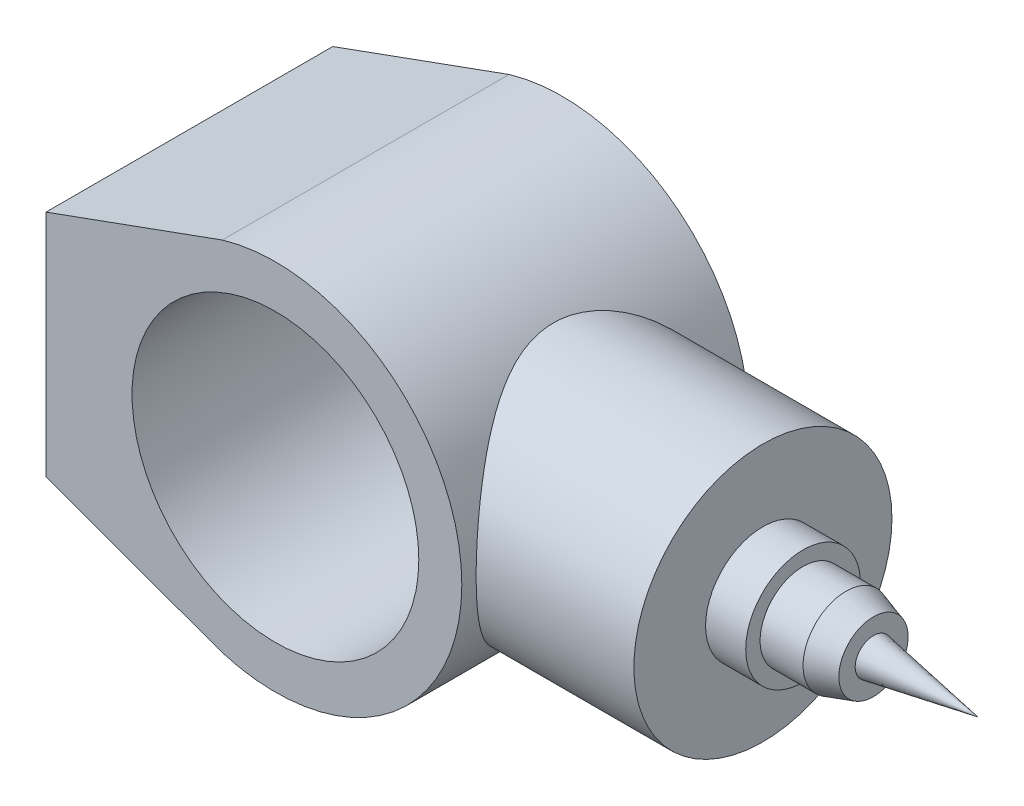
SolidWorks part; units mm, degrees
ref_plane "Front Plane" through (0, 0, 0) normal (0, 0, 1) x (1, 0, 0)
ref_plane "Top Plane" through (0, 0, 0) normal (0, 1, 0) x (1, 0, 0)
ref_plane "Right Plane" through (0, 0, 0) normal (1, 0, 0) x (0, 0, -1)
sketch "Sketch1" plane through (0, 0, 0) normal (0, 0, 1) x (1, 0, 0)
  line L0 (-80, -40) -> (-80, 40)
  line L1 (-80, 40) -> (-18.5119, 62.3082)
  line L2 (-80, -40) -> (-18.5119, -62.3082)
  arc A0 (-18.5119, -62.3082) -> (-18.5119, 62.3082) centre (0, 0) ccw
  circle A1 centre (0, 0) radius 50
  point P7 (-80, 0)
  dimension "D1" = 130
  dimension "D2" = 100
  dimension "D3" = 80
  dimension "D4" = 80
extrude "Boss-Extrude1" add sketch "Sketch1" along normal mid plane 100
ref_plane "Plane1" through (120, 0, 0) normal (1, 0, 0) x (0, 0, -1)
sketch "Sketch2" plane through (120, 0, 0) normal (1, 0, 0) x (0, 0, -1)
  circle A0 centre (0, 0) radius 45
  dimension "D1" = 90
extrude "Boss-Extrude2" add sketch "Sketch2" against normal up to next
sketch "Sketch3" plane through (0, 0, 0) normal (0, 0, 1) x (1, 0, 0)
  line L0 (0, 0) -> (320.8767, 0) construction
  line L1 (120, 0) -> (120, -20)
  line L2 (120, -45) -> (120, 45) construction
  line L3 (120, -20) -> (134, -20)
  line L4 (134, -20) -> (134, -15)
  line L5 (134, -15) -> (149, -15)
  line L6 (149, -15) -> (149, -15.0222)
  line L7 (149, -15.0222) -> (158.5555, -12.0741)
  line L8 (158.5555, -12.0741) -> (158.5555, -6.3876)
  line L9 (158.5555, -6.3876) -> (195, 0)
  line L10 (120, 0) -> (195, 0)
  point P16 (154.2443, -19.2854)
  dimension "D1" = 20
  dimension "D2" = 14
  dimension "D3" = 5
  dimension "D4" = 15
  dimension "D5" = 10
  dimension "D6" = 37
  dimension "D7" = 75
revolve "Revolve1" add sketch "Sketch3" angle 360 about L0
